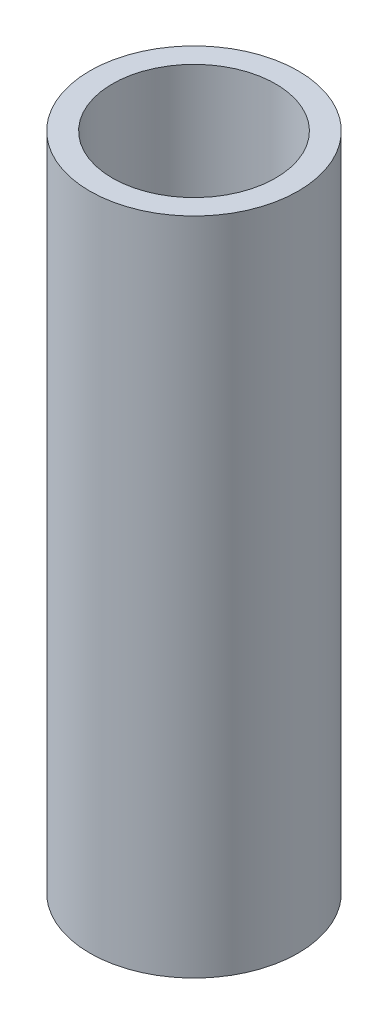
SolidWorks part; units mm, degrees
ref_plane "Front Plane" through (0, 0, 0) normal (0, 0, 1) x (1, 0, 0)
ref_plane "Top Plane" through (0, 0, 0) normal (0, 1, 0) x (1, 0, 0)
ref_plane "Right Plane" through (0, 0, 0) normal (1, 0, 0) x (0, 0, -1)
sketch "Sketch1" plane through (0, 0, 0) normal (0, 0, 1) x (1, 0, 0)
  line L0 (0, 21.4714) -> (0, 0) construction
  line L2 (-3, 0) -> (-2.35, 0)
  line L3 (-3, 0) -> (-3, 19)
  line L4 (-3, 19) -> (-2.35, 19)
  line L5 (-2.35, 0) -> (-2.35, 19)
  dimension "D1" = 19
  dimension "D3" = 4.7
  dimension "D2" = 6
revolve "Revolve1" add sketch "Sketch1" angle 360 about L0
equation "\"mid spacing\"= 4mm"
equation "\"bottom spacing\"= 19mm"
equation "\"top spacing\"= 19mm"
equation "\"D1@Sketch1\"    = \"top spacing\""
equation "\"Hole Tolerance\"= 0.5mm"
equation "\"D3@Sketch1\"=4.2 + \"Hole Tolerance\""
